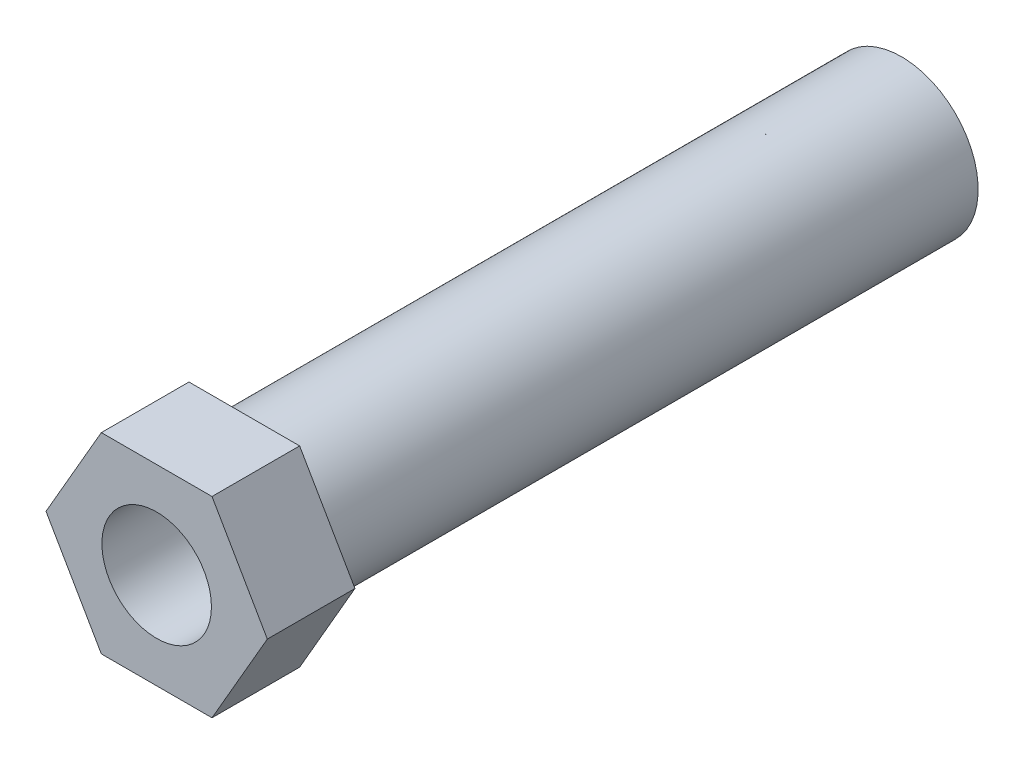
SolidWorks part; units mm, degrees
ref_plane "前视基准面" through (0, 0, 0) normal (0, 0, 1) x (1, 0, 0)
ref_plane "上视基准面" through (0, 0, 0) normal (0, 1, 0) x (1, 0, 0)
ref_plane "右视基准面" through (0, 0, 0) normal (1, 0, 0) x (0, 0, -1)
sketch "草图1" plane through (0, 0, 0) normal (0, 0, 1) x (1, 0, 0)
  line L1 (5.0518, 0) -> (2.5259, 4.375)
  line L2 (2.5259, 4.375) -> (-2.5259, 4.375)
  line L3 (-2.5259, 4.375) -> (-5.0518, 0)
  line L4 (-5.0518, 0) -> (-2.5259, -4.375)
  line L5 (-2.5259, -4.375) -> (2.5259, -4.375)
  line L6 (2.5259, -4.375) -> (5.0518, 0)
  circle A0 centre (0, 0) radius 4.375 construction
extrude "凸台-拉伸1" add sketch "草图1" along normal blind 4
sketch "草图2" plane through (0, 0, 0) normal (0, 0, -1) x (-1, 0, 0)
  circle A0 centre (0, 0) radius 2.5
  circle A1 centre (0, 0) radius 3.5
  dimension "D1" = 7
  dimension "D2" = 5
extrude "凸台-拉伸2" add sketch "草图2" along normal blind 30
sketch "草图3" plane through (0, 0, 4) normal (0, 0, 1) x (1, 0, 0)
  circle A0 centre (0, 0) radius 2.5
extrude "切除-拉伸1" cut sketch "草图3" against normal blind 64
